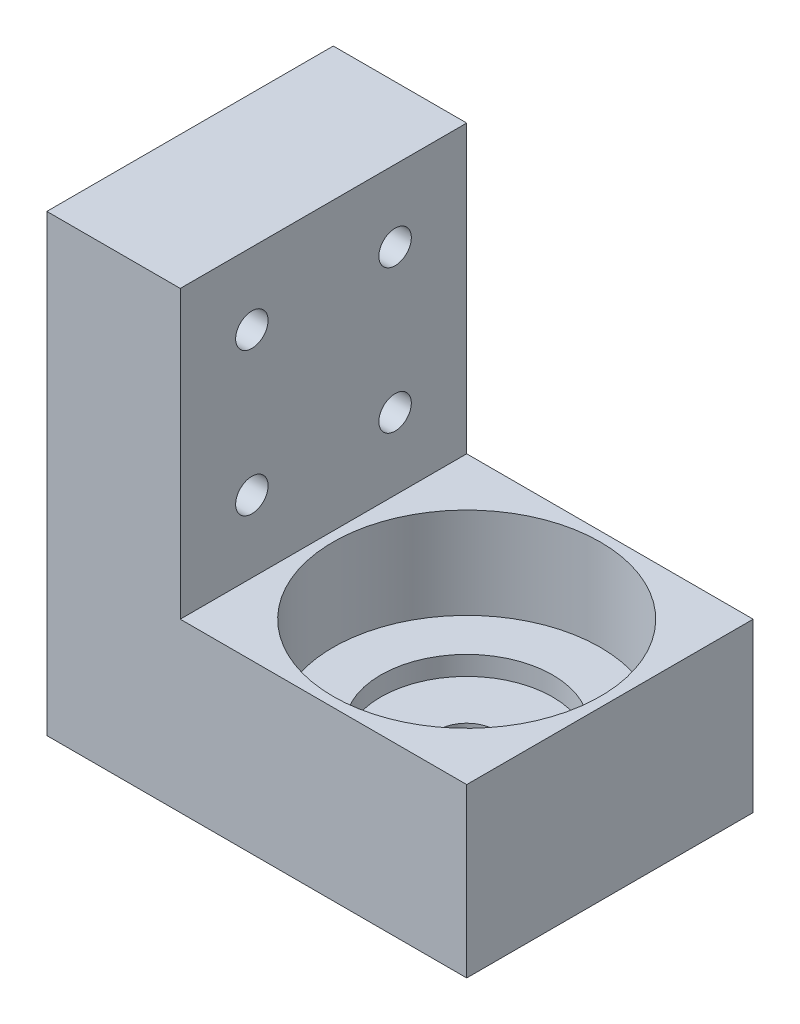
SolidWorks part; units mm, degrees
ref_plane "Front Plane" through (0, 0, 0) normal (0, 0, 1) x (1, 0, 0)
ref_plane "Top Plane" through (0, 0, 0) normal (0, 1, 0) x (1, 0, 0)
ref_plane "Right Plane" through (0, 0, 0) normal (1, 0, 0) x (0, 0, -1)
sketch "Sketch3" plane through (0, 0, 0) normal (0, 1, 0) x (1, 0, 0)
  line L1 (0, 0) -> (30, 0)
  line L2 (0, 0) -> (0, 30)
  line L3 (0, 30) -> (30, 30)
  line L4 (30, 0) -> (30, 30)
  dimension "D1" = 30
  dimension "D2" = 30
extrude "Boss-Extrude2" add sketch "Sketch3" along normal blind 17.5441
sketch "Sketch8" plane through (0, 17.5441, 0) normal (0, 1, 0) x (1, 0, 0)
  line L0 (15, 0) -> (15, 30) construction
  line L1 (0, 0) -> (30, 0) construction
  line L2 (30, 30) -> (0, 30) construction
  line L3 (30, 0) -> (30, 30) construction
  line L4 (30, 15) -> (0, 15) construction
  line L5 (0, 30) -> (0, 0) construction
  circle A0 centre (15, 15) radius 14
  dimension "D1" = 15
  dimension "D2" = 15
extrude "Cut-Extrude1" cut sketch "Sketch8" against normal blind 9.554
sketch "Sketch9" plane through (0, 7.9901, 0) normal (0, 1, 0) x (1, 0, 0)
  line L0 (15, 0) -> (15, 30.0855) construction
  line L1 (30, 0) -> (30, 30) construction
  line L2 (-0.1886, 15) -> (30.1886, 15) construction
  line L3 (30, 30) -> (0, 30) construction
  circle A0 centre (15, 15) radius 9
  dimension "D1" = 15
  dimension "D2" = 15
extrude "Cut-Extrude2" cut sketch "Sketch9" against normal blind 2
sketch "Sketch10" plane through (0, 5.9901, 0) normal (0, 1, 0) x (1, 0, 0)
  circle A0 centre (15, 15) radius 3
extrude "Cut-Extrude3" cut sketch "Sketch10" against normal through all
sketch "Sketch13" plane through (0, 0, 0) normal (-1, 0, 0) x (0, 0, 1)
  line L1 (-30, 0) -> (0, 0)
  line L2 (-30, 0) -> (-30, 47.5441)
  line L3 (-30, 47.5441) -> (0, 47.5441)
  line L4 (0, 0) -> (0, 47.5441)
  dimension "D1" = 30
  dimension "D2" = 47.5441
extrude "Boss-Extrude3" add sketch "Sketch13" along normal blind 13.9728
sketch "Sketch14" plane through (0, 0, 0) normal (1, 0, 0) x (0, 0, -1)
  line L0 (7.5, 47.5441) -> (7.5, 16.6434) construction
  line L1 (0, 47.5441) -> (30, 47.5441) construction
  line L2 (0, 17.5441) -> (0, 47.5441) construction
  line L3 (22.5, 47.5441) -> (22.5, 16.6434) construction
  line L4 (30, 47.5441) -> (30, 17.5441) construction
  circle A0 centre (7.5, 25.054) radius 1.7
  circle A1 centre (7.5, 40.054) radius 1.7
  circle A2 centre (22.5, 25.054) radius 1.7
  circle A3 centre (22.5, 40.054) radius 1.7
  dimension "D1" = 7.5
  dimension "D2" = 7.5
extrude "Cut-Extrude4" cut sketch "Sketch14" against normal through all
equation "\"del\"= .3mm"
equation "\"FS\"= 3"
equation "\"P\"= 300"
equation "\"L\"= 30mm"
equation "\"E\"= 2000"
equation "\"sig\"= 50000000"
equation "\"b\"= 18mm"
equation "\"MS\"= 12mm"
equation "\"M1\"= \"P\" * \"MS\" * \"FS\""
equation "\"h1\"= ( ( 6 * \"M1\" * ( \"L\" ^ 2 ) ) / ( \"E\" * \"b\" * \"del\" ) ) ^ ( 1 / 3 )"
equation "\"M2\"= \"P\" * ( \"MS\" + \"h1\" ) * ( 3 )"
equation "\"h2\"= ( ( 6 * \"M2\" * \"h1\" ^ 2 ) / ( \"E\" * \"L\" * \"del\" ) ) ^ ( 1 / 3 )"
equation "\"D1@Sketch3\"= \"L\""
equation "\"D2@Sketch3\"=\"L\""
equation "\"D1@Boss-Extrude2\"=\"h1\""
equation "\"D1@Sketch8\"=\"L\"/2"
equation "\"D2@Sketch8\"=\"L\"/2"
equation "\"D1@Sketch9\"=\"L\"/2"
equation "\"D2@Sketch9\"=\"L\"/2"
equation "\"D1@Sketch13\"=\"L\""
equation "\"D2@Sketch13\"= \"L\" + \"h1\""
equation "\"D1@Boss-Extrude3\"=\"h2\""
equation "\"D1@Sketch14\"=\"L\" / 4"
equation "\"D2@Sketch14\"=\"L\" /4"
